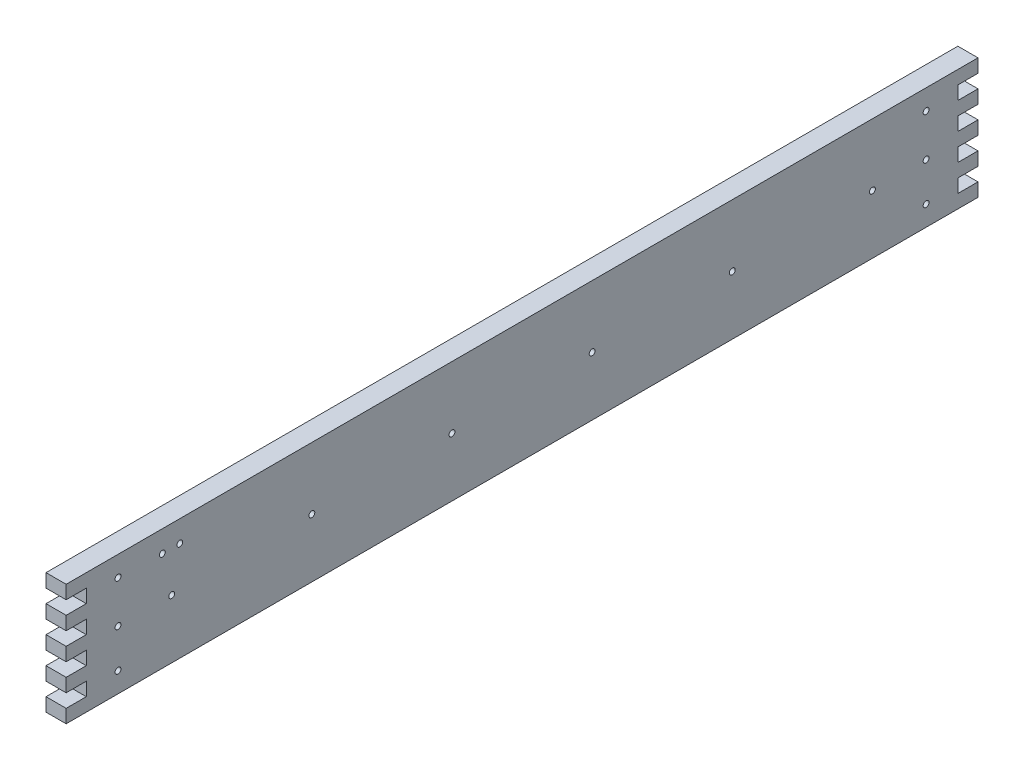
SolidWorks part; units mm, degrees
material "Pine"
ref_plane "Front Plane" through (0, 0, 0) normal (0, 0, 1) x (1, 0, 0)
ref_plane "Top Plane" through (0, 0, 0) normal (0, 1, 0) x (1, 0, 0)
ref_plane "Right Plane" through (0, 0, 0) normal (1, 0, 0) x (0, 0, -1)
sketch "Sketch1" plane through (0, 0, 0) normal (1, 0, 0) x (0, 0, -1)
  line L0 (19.05, 114.3) -> (19.05, 101.6) construction
  line L1 (0, 0) -> (862.33, 0)
  line L2 (0, 0) -> (0, 12.7)
  line L3 (0, 114.3) -> (862.33, 114.3)
  line L4 (862.33, 0) -> (862.33, 12.7)
  line L5 (0, 0) -> (862.33, 114.3) construction
  line L6 (0, 114.3) -> (862.33, 0) construction
  line L7 (0, 101.6) -> (19.05, 101.6)
  line L9 (0, 88.9) -> (19.05, 88.9)
  line L10 (0, 76.2) -> (19.05, 76.2)
  line L12 (0, 63.5) -> (19.05, 63.5)
  line L13 (19.05, 76.2) -> (19.05, 63.5)
  line L14 (0, 76.2) -> (19.05, 63.5) construction
  line L15 (0, 63.5) -> (19.05, 76.2) construction
  line L16 (0, 50.8) -> (19.05, 50.8)
  line L18 (0, 38.1) -> (19.05, 38.1)
  line L19 (19.05, 50.8) -> (19.05, 38.1)
  line L20 (0, 50.8) -> (19.05, 38.1) construction
  line L21 (0, 38.1) -> (19.05, 50.8) construction
  line L22 (0, 25.4) -> (19.05, 25.4)
  line L24 (0, 12.7) -> (19.05, 12.7)
  line L25 (19.05, 25.4) -> (19.05, 12.7)
  line L26 (0, 25.4) -> (19.05, 12.7) construction
  line L27 (0, 12.7) -> (19.05, 25.4) construction
  line L28 (19.05, 101.6) -> (19.05, 88.9)
  line L29 (0, 101.6) -> (19.05, 88.9) construction
  line L30 (0, 88.9) -> (19.05, 101.6) construction
  line L31 (19.05, 88.9) -> (19.05, 76.2) construction
  line L32 (19.05, 63.5) -> (19.05, 50.8) construction
  line L33 (19.05, 38.1) -> (19.05, 25.4) construction
  line L34 (19.05, 12.7) -> (19.05, 0) construction
  line L35 (0, 101.6) -> (0, 114.3)
  line L36 (0, 76.2) -> (0, 88.9)
  line L37 (0, 50.8) -> (0, 63.5)
  line L38 (0, 25.4) -> (0, 38.1)
  line L39 (431.165, 114.3) -> (431.165, 0) construction
  line L40 (862.33, 12.7) -> (843.28, 12.7)
  line L41 (843.28, 25.4) -> (843.28, 12.7)
  line L42 (862.33, 25.4) -> (843.28, 25.4)
  line L43 (862.33, 38.1) -> (843.28, 38.1)
  line L44 (843.28, 50.8) -> (843.28, 38.1)
  line L45 (862.33, 50.8) -> (843.28, 50.8)
  line L46 (862.33, 63.5) -> (843.28, 63.5)
  line L47 (843.28, 76.2) -> (843.28, 63.5)
  line L48 (862.33, 76.2) -> (843.28, 76.2)
  line L49 (862.33, 88.9) -> (843.28, 88.9)
  line L50 (843.28, 101.6) -> (843.28, 88.9)
  line L51 (862.33, 101.6) -> (843.28, 101.6)
  line L52 (862.33, 101.6) -> (862.33, 114.3)
  line L53 (862.33, 76.2) -> (862.33, 88.9)
  line L54 (862.33, 50.8) -> (862.33, 63.5)
  line L55 (862.33, 25.4) -> (862.33, 38.1)
  point P4 (431.165, 57.15)
  point P14 (9.525, 69.85)
  point P19 (9.525, 44.45)
  point P24 (9.525, 19.05)
  point P25 (9.525, 95.25)
  dimension "D1" = 12.7
  dimension "D2" = 19.05
  dimension "D3" = 114.3
  dimension "D4" = 824.23
extrude "Boss-Extrude1" add sketch "Sketch1" along normal blind 19.05
hole_wizard "7/32 (0.21875) Diameter Hole2" positions "Sketch2" profile "Sketch3" hole size "7/32" standard "ANSI Inch" end condition up to next
sketch "Sketch2" plane through (19.05, 0, 0) normal (1, 0, 0) x (0, 0, -1)
  line L0 (49.0601, 55.499) -> (99.8601, 55.499) construction
  line L1 (99.8601, 55.499) -> (232.3821, 55.499) construction
  line L2 (232.3821, 55.499) -> (364.904, 55.499) construction
  line L3 (364.904, 55.499) -> (497.426, 55.499) construction
  line L4 (497.426, 55.499) -> (629.9479, 55.499) construction
  line L5 (629.9479, 55.499) -> (762.4699, 55.499) construction
  line L6 (762.4699, 55.499) -> (813.2699, 55.499) construction
  line L8 (813.2699, 95.25) -> (813.2699, 19.05) construction
  line L10 (49.0601, 95.25) -> (49.0601, 19.05) construction
  line L12 (49.0601, 19.05) -> (49.0601, 0) construction
  line L13 (0, 0) -> (862.33, 0) construction
  line L15 (49.0601, 95.25) -> (49.0601, 114.3) construction
  line L16 (862.33, 114.3) -> (0, 114.3) construction
  line L19 (813.2699, 95.25) -> (813.2699, 114.3) construction
  line L21 (813.2699, 19.05) -> (813.2699, 0) construction
  line L22 (431.165, 114.3) -> (431.165, 0) construction
  line L29 (49.0601, 93.8784) -> (90.9683, 93.8784) construction
  line L30 (90.9683, 93.8784) -> (107.4783, 93.8784) construction
  point P1 (49.0601, 55.499)
  point P2 (99.8601, 55.499)
  point P4 (232.3821, 55.499)
  point P5 (364.904, 55.499)
  point P6 (497.426, 55.499)
  point P8 (629.9479, 55.499)
  point P10 (762.4699, 55.499)
  point P11 (813.2699, 55.499)
  point P13 (813.2699, 95.25)
  point P14 (813.2699, 19.05)
  point P18 (49.0601, 95.25)
  point P19 (49.0601, 19.05)
  point P100 (90.9683, 93.8784)
  point P103 (107.4783, 93.8784)
  dimension "D1" = 19.05
  dimension "D2" = 662.6098
  dimension "D3" = 55.499
  dimension "D4" = 764.2098
  dimension "D5" = 41.9082
  dimension "D11" = 16.51
  dimension "D12" = 38.3794
sketch "Sketch3" plane through (19.05, 55.499, -49.0601) normal (0, 1, 0) x (0, 0, -1)
  line L0 (0, 0) -> (0, 19.05)
  line L1 (0, 19.05) -> (2.7781, 19.05)
  line L2 (2.7781, 19.05) -> (2.7781, 0)
  line L5 (2.7781, 0) -> (0, 0)
  line L11 (0, -6.35) -> (0, 107.95) construction
  dimension "Thru Hole Dia." = 5.5562
  dimension "Thru Hole Depth" = 19.05
